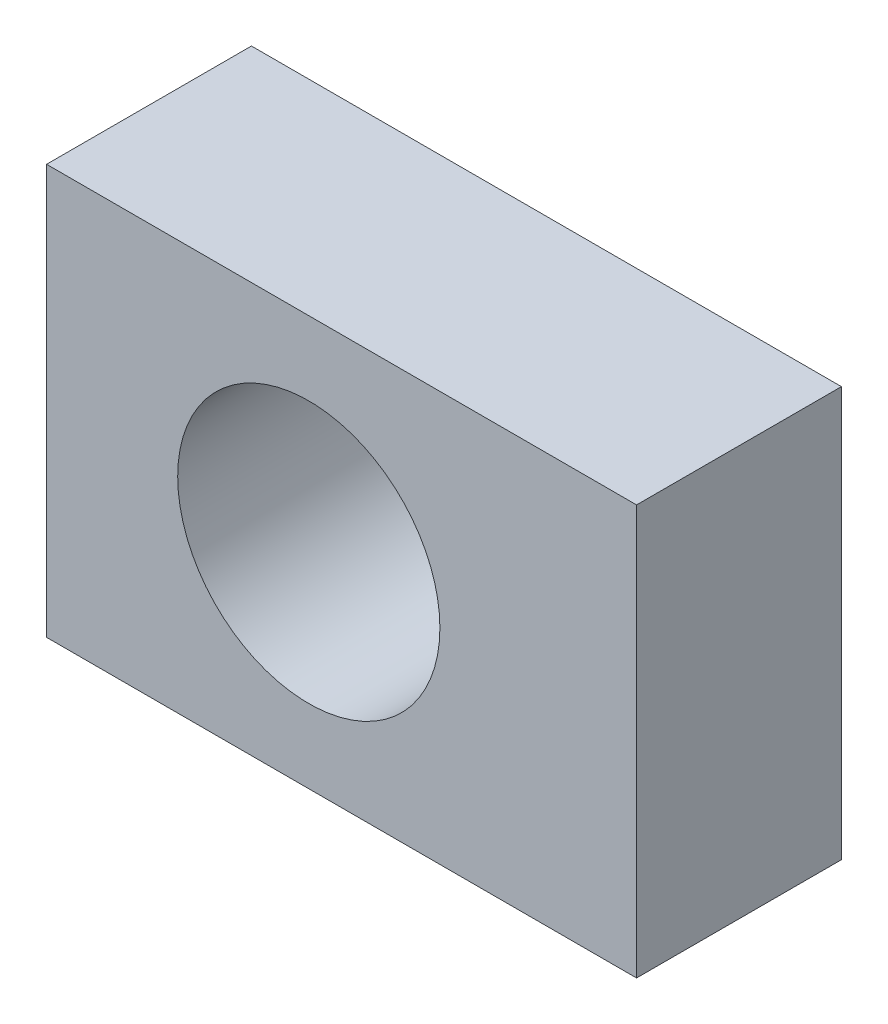
SolidWorks part; units mm, degrees
ref_plane "Front Plane" through (0, 0, 0) normal (0, 0, 1) x (1, 0, 0)
ref_plane "Top Plane" through (0, 0, 0) normal (0, 1, 0) x (1, 0, 0)
ref_plane "Right Plane" through (0, 0, 0) normal (1, 0, 0) x (0, 0, -1)
sketch "Sketch4" plane through (0, 0, 0) normal (0, 0, 1) x (1, 0, 0)
  line L1 (0, 0) -> (9.144, 0)
  line L2 (0, 0) -> (0, -6.35)
  line L3 (0, -6.35) -> (9.144, -6.35)
  line L4 (9.144, 0) -> (9.144, -6.35)
  circle A0 centre (4.064, -3.175) radius 2.032
  dimension "D4" = 4.064
  dimension "D1" = 9.144
  dimension "D2" = 6.35
extrude "Boss-Extrude2" add sketch "Sketch4" along normal blind 3.175
